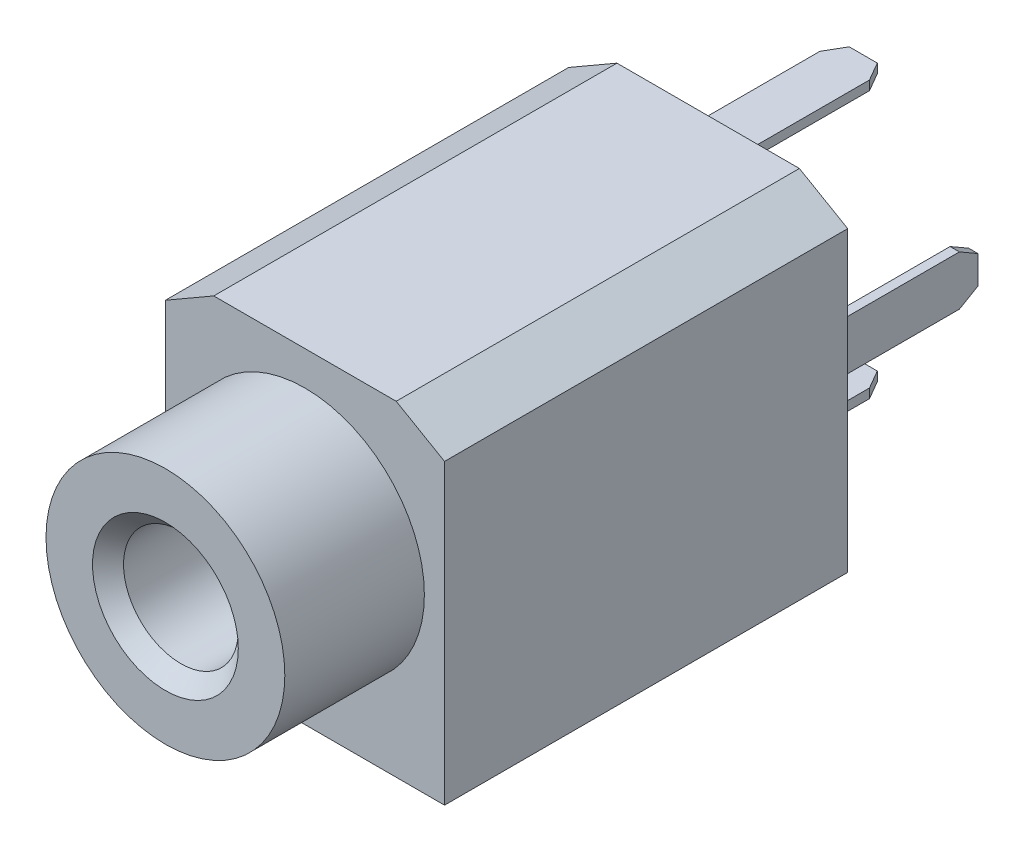
SolidWorks part; units mm, degrees
ref_plane "Front Plane" through (0, 0, 0) normal (0, 0, 1) x (1, 0, 0)
ref_plane "Top Plane" through (0, 0, 0) normal (0, 1, 0) x (1, 0, 0)
ref_plane "Right Plane" through (0, 0, 0) normal (1, 0, 0) x (0, 0, -1)
sketch "Sketch1" plane through (0, 0, 0) normal (0, 0, 1) x (1, 0, 0)
  circle A0 centre (0, 0) radius 3.85
  dimension "D1" = 7.7
extrude "Boss-Extrude1" add sketch "Sketch1" along normal blind 4.5
sketch "Sketch2" plane through (0, 0, 0) normal (0, 0, -1) x (-1, 0, 0)
  line L0 (0, 4.95) -> (0, -5.55) construction
  line L1 (-4.5, 4.95) -> (4.5, 4.95)
  line L2 (-4.5, 4.95) -> (-4.5, -5.55)
  line L3 (-4.5, -5.55) -> (4.5, -5.55)
  line L4 (4.5, 4.95) -> (4.5, -5.55)
  circle A0 centre (0, 0) radius 3.85 construction
  point P5 (0, 3.85)
  dimension "D1" = 9
  dimension "D2" = 10.5
  dimension "D3" = 1.1
extrude "Boss-Extrude2" add sketch "Sketch2" along normal blind 13
chamfer "Chamfer1" distance 0.9 angle 60 2 edges at (4.5, 4.95, -6.5) (-4.5, 4.95, -6.5)
sketch "Sketch3" plane through (0, 0, -13) normal (0, 0, -1) x (-1, 0, 0)
  line L0 (-3.4, 0) -> (3.4, 0) construction
  line L1 (-0.8, 4.15) -> (0.8, 4.15)
  line L2 (-0.8, 4.15) -> (-0.8, 3.85)
  line L3 (-0.8, 3.85) -> (0.8, 3.85)
  line L4 (0.8, 4.15) -> (0.8, 3.85)
  line L5 (3.4, 0.8) -> (3.7, 0.8)
  line L6 (3.4, 0.8) -> (3.4, -0.8)
  line L7 (3.4, -0.8) -> (3.7, -0.8)
  line L8 (3.7, 0.8) -> (3.7, -0.8)
  line L9 (-3.7, 0.8) -> (-3.4, 0.8)
  line L10 (-3.7, 0.8) -> (-3.7, -0.8)
  line L11 (-3.7, -0.8) -> (-3.4, -0.8)
  line L12 (-3.4, 0.8) -> (-3.4, -0.8)
  line L13 (-0.8, -4.45) -> (0.8, -4.45)
  line L14 (-0.8, -4.45) -> (-0.8, -4.75)
  line L15 (-0.8, -4.75) -> (0.8, -4.75)
  line L16 (0.8, -4.45) -> (0.8, -4.75)
  line L17 (-4.5, 4.05) -> (-4.5, -5.55) construction
  line L18 (0, 3.85) -> (0, -4.45) construction
  line L19 (2.9412, 4.95) -> (-2.9412, 4.95) construction
  line L20 (-4.5, -5.55) -> (4.5, -5.55) construction
  dimension "D1" = 1.6
  dimension "D2" = 0.3
  dimension "D3" = 1.6
  dimension "D4" = 0.3
  dimension "D5" = 0.8
  dimension "D6" = 0.8
  dimension "D7" = 0.8
extrude "Boss-Extrude3" add sketch "Sketch3" along normal blind 5
chamfer "Chamfer2" distance 0.6 angle 30 8 edges at (0.8, 4, -18) (-0.8, 4, -18) (3.55, 0.8, -18) (3.55, -0.8, -18) (0.8, -4.6, -18) (-0.8, -4.6, -18) (-3.55, -0.8, -18) (-3.55, 0.8, -18)
sketch "Sketch4" plane through (0, 0, 4.5) normal (0, 0, 1) x (1, 0, 0)
  circle A0 centre (0, 0) radius 1.85
  dimension "D1" = 3.7
extrude "Cut-Extrude1" cut sketch "Sketch4" against normal up to surface (17.5 mm away) up to face at (0, 1.15, -13)
chamfer "Chamfer3" distance 0.5 angle 45 1 edges at (1.85, 0, 4.5)
